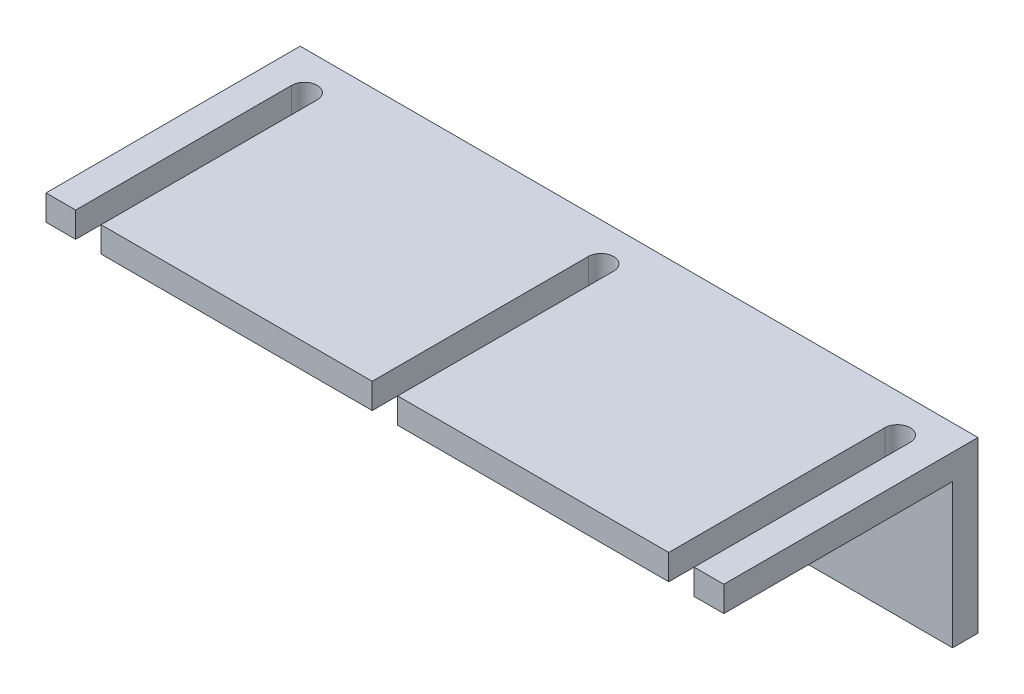
SolidWorks part; units mm, degrees
ref_plane "前视基准面" through (0, 0, 0) normal (0, 0, 1) x (1, 0, 0)
ref_plane "上视基准面" through (0, 0, 0) normal (0, 1, 0) x (1, 0, 0)
ref_plane "右视基准面" through (0, 0, 0) normal (1, 0, 0) x (0, 0, -1)
other "Configuration Table"
sketch "草图1" plane through (0, 0, 0) normal (0, 0, 1) x (1, 0, 0)
  line L0 (0, 0) -> (50000, 0) construction
  line L1 (-40, 10) -> (40, 10)
  line L2 (-40, 10) -> (-40, -10)
  line L3 (-40, -10) -> (40, -10)
  line L4 (40, 10) -> (40, -10)
  line L5 (-40, 10) -> (40, -10) construction
  line L6 (-40, -10) -> (40, 10) construction
  circle A0 centre (20, 0) radius 3
  circle A1 centre (-20, 0) radius 3
  point P0 (0, 0)
  dimension "D4" = 6
  dimension "D5" = 6
  dimension "D1" = 20
  dimension "D2" = 80
  dimension "D3" = 20
  dimension "D6" = 20
extrude "凸台-拉伸1" add sketch "草图1" along normal blind 3
sketch "草图2" plane through (0, 10, 0) normal (0, 1, 0) x (1, 0, 0)
  line L0 (40, -3) -> (40, 0) construction
  line L1 (-40, 0) -> (40, 0)
  line L2 (-40, 0) -> (-40, -30)
  line L3 (-40, -30) -> (40, -30)
  line L4 (40, 0) -> (40, -30)
  dimension "D1" = 30
extrude "凸台-拉伸2" add sketch "草图2" against normal blind 3
sketch "草图3" plane through (0, 10, 0) normal (0, 1, 0) x (1, 0, 0)
  line L0 (-36.5, -30) -> (-36.5, -4.5)
  line L1 (-40, -30) -> (40, -30) construction
  line L3 (-33.5, -4.5) -> (-33.5, -30)
  line L4 (0, 0) -> (0, -50000) construction
  line L5 (40, 0) -> (-40, 0) construction
  line L6 (-40, -30) -> (-40, 0) construction
  line L7 (-36.5, -30) -> (-33.5, -30)
  line L8 (-35, -4.5) -> (49965, -4.5) construction
  line L9 (-1.5, -4.5) -> (-1.5, -30)
  line L10 (-1.5, -30) -> (1.5, -30)
  line L11 (1.5, -30) -> (1.5, -4.5)
  line L12 (36.5, -4.5) -> (36.5, -30)
  line L13 (36.5, -30) -> (33.5, -30)
  line L14 (33.5, -30) -> (33.5, -4.5)
  line L15 (40, -30) -> (40, 0) construction
  arc A0 (-36.5, -4.5) -> (-33.5, -4.5) centre (-35, -4.5) cw
  arc A1 (-1.5, -4.5) -> (1.5, -4.5) centre (0, -4.5) cw
  arc A2 (33.5, -4.5) -> (36.5, -4.5) centre (35, -4.5) cw
  point P10 (0, 0)
  point P30 (36.6112, -4.5335)
  line M16 (-40, -30) -> (40, -30)
  dimension "D1" = 3.5
  dimension "D2" = 3
  dimension "D3" = 1.5
  dimension "D4" = 1.5
  dimension "D5" = 3
  dimension "D6" = 3.5
  dimension "D7" = 4.5
extrude "切除-拉伸1" cut sketch "草图3" against normal blind 20 contours A1 L9 L11 M16 | A2 L14 L12 M16 | A0 L0 L3 M16
